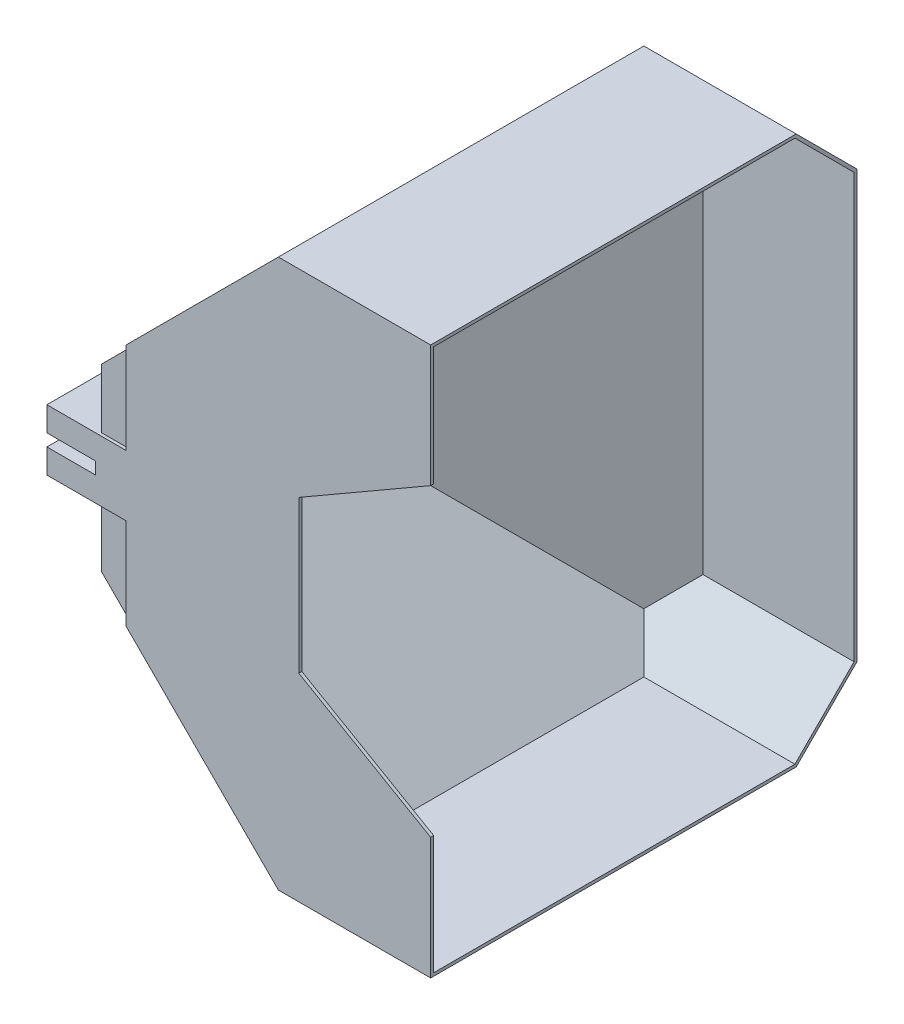
SolidWorks part; units mm, degrees
ref_plane "Front Plane" through (0, 0, 0) normal (0, 0, 1) x (1, 0, 0)
ref_plane "Top Plane" through (0, 0, 0) normal (0, 1, 0) x (1, 0, 0)
ref_plane "Right Plane" through (0, 0, 0) normal (1, 0, 0) x (0, 0, -1)
sketch "Sketch1" plane through (0, 0, 0) normal (0, 1, 0) x (1, 0, 0)
  line L1 (-27.5, 35) -> (27.5, 35)
  line L2 (-27.5, 35) -> (-27.5, -35)
  line L3 (-27.5, -35) -> (27.5, -35)
  line L4 (27.5, 35) -> (27.5, -35)
  line L5 (-27.5, 35) -> (27.5, -35) construction
  line L6 (-27.5, -35) -> (27.5, 35) construction
  point P0 (0, 0)
  dimension "D1" = 55
  dimension "D2" = 70
extrude "Boss-Extrude1" add sketch "Sketch1" along normal blind 90
chamfer "Chamfer1" distance 30 angle 45 1 edges at (-27.5, 45, -35)
chamfer "Chamfer2" distance 30 angle 45 2 edges at (-27.5, 0, 15) (-27.5, 90, 15)
chamfer "Chamfer3" distance 10 angle 45 2 edges at (15, 90, -35) (15, 0, -35)
shell "Shell1" thickness 0.5
sketch "Sketch2" plane through (-27.5, 0, 0) normal (-1, 0, 0) x (0, 0, 1)
  line L0 (35, 45) -> (15, 45)
  line L1 (35, 60) -> (35, 30) construction
  line L3 (15, 40) -> (35, 40)
  line L4 (15, 40) -> (15, 50)
  line L5 (15, 50) -> (35, 50)
  line L6 (35, 40) -> (35, 50)
  line L7 (15, 40) -> (35, 50) construction
  line L8 (15, 50) -> (35, 40) construction
  point P4 (25, 45)
  line M5 (35, 30) -> (35, 60)
  dimension "D1" = 20
  dimension "D2" = 10
extrude "Boss-Extrude2" add sketch "Sketch2" along normal blind 8 contours L5 L4 L0 M5 | L4 L3 L0 M5
fillet "Fillet1" radius 5 1 edges at (-35.5, 45, 15)
sketch "Sketch3" plane through (-35.5, 0, 0) normal (-1, 0, 0) x (0, 0, 1)
  line L0 (35, 40) -> (35, 50) construction
  line L1 (50, 44) -> (20, 44)
  line L2 (50, 44) -> (50, 46)
  line L3 (50, 46) -> (20, 46)
  line L4 (20, 44) -> (20, 46)
  line L5 (50, 44) -> (20, 46) construction
  line L6 (50, 46) -> (20, 44) construction
  line L7 (20, 50) -> (20, 40) construction
  point P0 (35, 45)
  dimension "D1" = 2
extrude "Cut-Extrude1" cut sketch "Sketch3" against normal blind 8
chamfer "Chamfer5" distance 5 angle 45 2 edges at (-27.5, 35, 35) (-27.5, 55, 35)
sketch "Sketch4" plane through (0, 0, 34.5) normal (0, 0, -1) x (-1, 0, 0)
  line L0 (-27.5, 90) -> (-27.5, 0) construction
  line L1 (-27.5, 70) -> (-49.1506, 57.5)
  line L2 (-49.1506, 57.5) -> (-49.1506, 32.5)
  line L3 (-49.1506, 32.5) -> (-27.5, 20)
  line L4 (-27.5, 20) -> (-5.8494, 32.5)
  line L5 (-5.8494, 32.5) -> (-5.8494, 57.5)
  line L6 (-5.8494, 57.5) -> (-27.5, 70)
  circle A0 centre (-27.5, 45) radius 21.6506 construction
  dimension "D1" = 25
extrude "Cut-Extrude2" cut sketch "Sketch4" against normal mid plane 10 contours L1 L2 L3 L4 L5 L6
